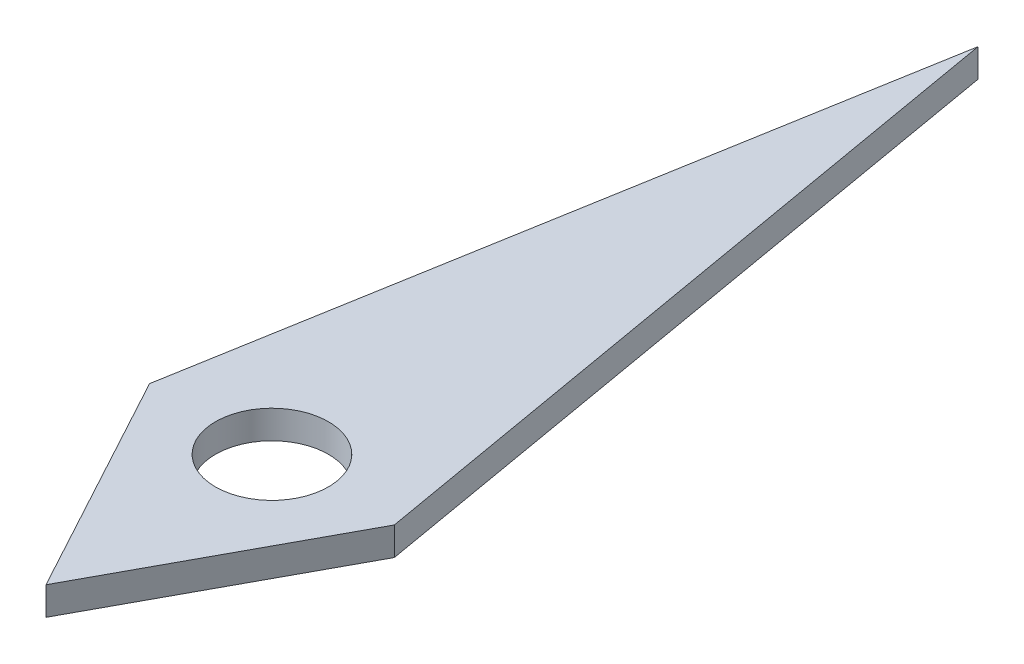
SolidWorks part; units mm, degrees
ref_plane "Front Plane" through (0, 0, 0) normal (0, 0, 1) x (1, 0, 0)
ref_plane "Top Plane" through (0, 0, 0) normal (0, 1, 0) x (1, 0, 0)
ref_plane "Right Plane" through (0, 0, 0) normal (1, 0, 0) x (0, 0, -1)
sketch "Sketch2" plane through (0, 0, 0) normal (0, 1, 0) x (1, 0, 0)
  line L4 (-1.3, 0) -> (0, 7.5)
  line L5 (0, 7.5) -> (1.3, 0)
  line L6 (0, -2.4) -> (-1.3, 0)
  line L7 (0, -2.4) -> (1.3, 0)
extrude "Boss-Extrude1" add sketch "Sketch2" along normal blind 0.3
sketch "Sketch3" plane through (0, 0.3, 0) normal (0, 1, 0) x (1, 0, 0)
  circle A0 centre (0, 0) radius 0.6
extrude "Cut-Extrude1" cut sketch "Sketch3" against normal blind 0.3
